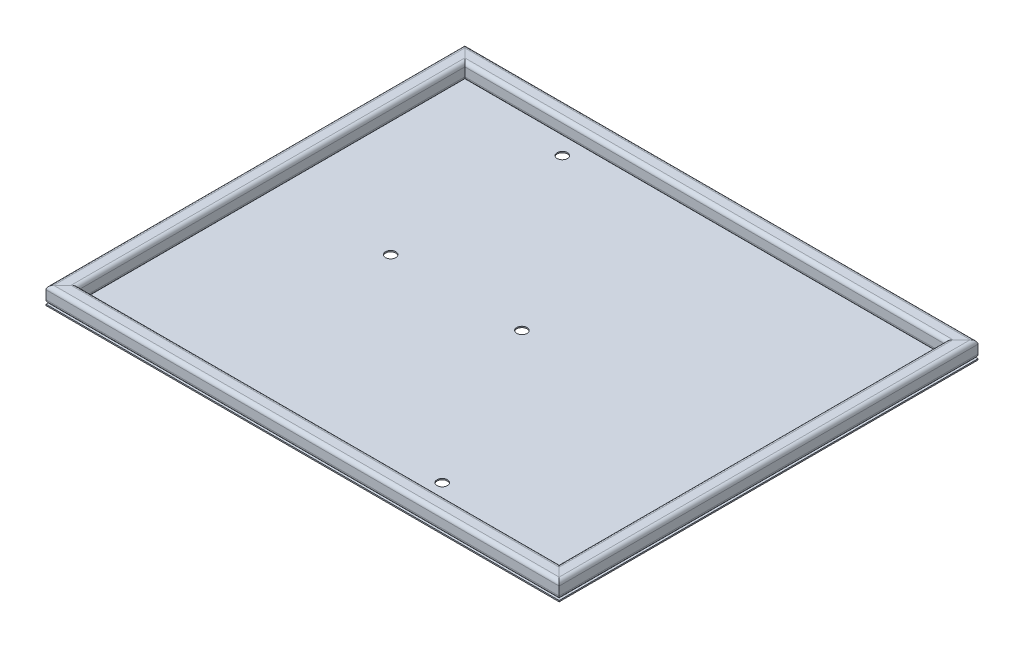
SolidWorks part; units mm, degrees
ref_plane "Alzado" through (0, 0, 0) normal (0, 0, 1) x (1, 0, 0)
ref_plane "Planta" through (0, 0, 0) normal (0, 1, 0) x (1, 0, 0)
ref_plane "Vista lateral" through (0, 0, 0) normal (1, 0, 0) x (0, 0, -1)
sketch "Croquis1" plane through (0, 0, 0) normal (0, 1, 0) x (1, 0, 0)
  line L1 (-398.2, 325) -> (398.2, 325)
  line L2 (-398.2, 325) -> (-398.2, -325)
  line L3 (-398.2, -325) -> (398.2, -325)
  line L4 (398.2, 325) -> (398.2, -325)
  line L5 (-398.2, 325) -> (398.2, -325) construction
  line L6 (-398.2, -325) -> (398.2, 325) construction
  point P0 (0, 0)
  dimension "D1" = 650
  dimension "D2" = 796.4
other "Tubo cuadrado 2 X 2 X 0.25(1)"
ref_plane "Plano1" through (-385.5, 12.7, -325) normal (0, 0, 1) x (1, 0, 0)
sketch "Sketch1" plane through (-385.5, 12.7, -325) normal (0, 0, 1) x (1, 0, 0)
  line L0 (-6.7, -9.7) -> (6.7, -9.7)
  line L1 (-9.7, -6.7) -> (-9.7, 6.7)
  line L2 (6.7, 9.7) -> (-6.7, 9.7)
  line L3 (9.7, 6.7) -> (9.7, -6.7)
  line L4 (-6.7, -12.7) -> (6.7, -12.7)
  line L5 (-12.7, -6.7) -> (-12.7, 6.7)
  line L6 (6.7, 12.7) -> (-6.7, 12.7)
  line L7 (12.7, 6.7) -> (12.7, -6.7)
  line L8 (0, 0) -> (9.7, 0) construction
  line L9 (0, 0) -> (0, 9.7) construction
  arc A0 (12.7, 6.7) -> (6.7, 12.7) centre (6.7, 6.7) ccw
  arc A1 (6.7, -12.7) -> (12.7, -6.7) centre (6.7, -6.7) ccw
  arc A2 (-12.7, -6.7) -> (-6.7, -12.7) centre (-6.7, -6.7) ccw
  arc A3 (-6.7, 12.7) -> (-12.7, 6.7) centre (-6.7, 6.7) ccw
  arc A4 (-6.7, 9.7) -> (-9.7, 6.7) centre (-6.7, 6.7) ccw
  arc A5 (9.7, 6.7) -> (6.7, 9.7) centre (6.7, 6.7) ccw
  arc A6 (6.7, -9.7) -> (9.7, -6.7) centre (6.7, -6.7) ccw
  arc A7 (-9.7, -6.7) -> (-6.7, -9.7) centre (-6.7, -6.7) ccw
  point P3 (0, 12.7)
  point P4 (12.7, 0)
  point P5 (0, -12.7)
  point P6 (-12.7, 0)
  point P7 (-12.7, 12.7)
  point P8 (-12.7, -12.7)
  point P33 (0, 0)
  point P35 (12.7, -12.7)
  point P36 (12.7, 12.7)
  point P37 (0, 0)
  dimension "D1" = 6
  dimension "Thickness" = 3
  dimension "V_leg" = 25.4
sketch "Croquis3" plane through (0, 0, 0) normal (0, -1, 0) x (1, 0, 0)
  line L1 (398.2, 325) -> (-398.2, 325)
  line L2 (398.2, 325) -> (398.2, -325)
  line L3 (398.2, -325) -> (-398.2, -325)
  line L4 (-398.2, 325) -> (-398.2, -325)
  line L5 (398.2, 325) -> (-398.2, -325) construction
  line L6 (398.2, -325) -> (-398.2, 325) construction
  point P0 (0, 0)
extrude "Saliente-Extruir1" add sketch "Croquis3" along normal blind 1.9 separate body
ref_plane "Plano2" through (0, 0, 250) normal (0, 0, 1) x (1, 0, 0)
sketch "Croquis4" plane through (0, 0, 0) normal (0, 1, 0) x (1, 0, 0)
  circle A3 centre (161.8, -258.5729) radius 7.9375
  circle A5 centre (0, -145.112) radius 7.9375
  circle A7 centre (-197.3, -145.2099) radius 7.9375
  circle A10 centre (-197.3, 274.7851) radius 7.9375
sketch "Croquis5" plane through (0, 0, 0) normal (0, 1, 0) x (1, 0, 0)
  line L0 (153.4217, -255.3659) -> (149.1, -257.3729) construction
  line L1 (149.1, -257.3729) -> (6.35, 9.025) construction
  line L2 (6.35, 9.025) -> (-197.3, 9.025) construction
  line L3 (-197.3, 9.025) -> (-197.3, 275.4228) construction
  circle A0 centre (149.1, -257.3729) radius 8
  circle A1 centre (6.35, 9.025) radius 8
  circle A2 centre (-197.3, 9.025) radius 8
  circle A3 centre (-197.3, 275.4228) radius 8
  dimension "D1" = 16
  dimension "D2" = 16
  dimension "D3" = 16
  dimension "D4" = 16
extrude "Cortar-Extruir1" cut sketch "Croquis5" against normal blind 10
